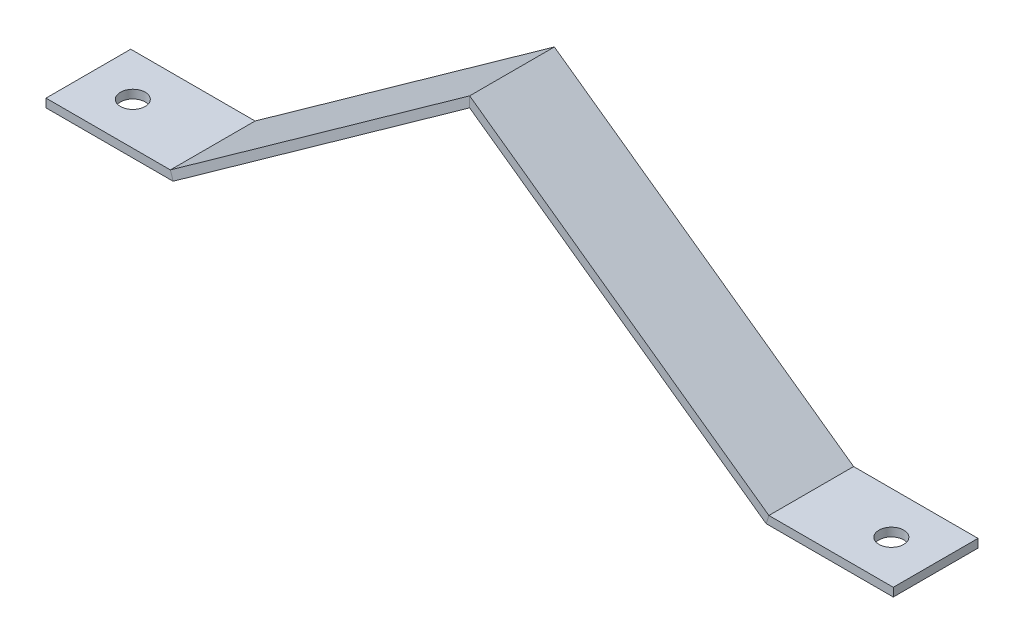
SolidWorks part; units mm, degrees
ref_plane "Front Plane" through (0, 0, 0) normal (0, 0, 1) x (1, 0, 0)
ref_plane "Top Plane" through (0, 0, 0) normal (0, 1, 0) x (1, 0, 0)
ref_plane "Right Plane" through (0, 0, 0) normal (1, 0, 0) x (0, 0, -1)
sketch "Sketch2" plane through (0, 0, 0) normal (0, 0, 1) x (1, 0, 0)
  line L0 (0, 0) -> (-3.81, 0)
  line L1 (-3.81, 0) -> (-12.7, 6.35)
  line L2 (-12.7, 6.35) -> (-21.59, 0)
  line L3 (-21.59, 0) -> (-25.4, 0)
  dimension "D1" = 25.4
  dimension "D2" = 17.78
  dimension "D3" = 8.89
  dimension "D4" = 6.35
  dimension "D5" = 3.81
sketch "Sketch3" plane through (0, 0, 0) normal (1, 0, 0) x (0, 0, -1)
  line L1 (0, 0) -> (2.54, 0)
  line L2 (0, 0) -> (0, 0.254)
  line L3 (0, 0.254) -> (2.54, 0.254)
  line L4 (2.54, 0) -> (2.54, 0.254)
  dimension "D1" = 2.54
  dimension "D2" = 0.254
sweep "Sweep1" add profiles "Sketch3" path "Sketch2"
hole_wizard "#69 (0.0292) Diameter Hole1" positions "Sketch5" profile "Sketch4" hole size "#69" standard "ANSI Inch" end condition through all
sketch "Sketch5" plane through (0, 0.254, 0) normal (0, 1, 0) x (1, 0, 0)
  line L0 (-21.6714, 0) -> (-25.4, 0) construction
  line L1 (-3.7286, 0) -> (0, 0) construction
  line L2 (-25.4, 0) -> (-25.4, 2.54) construction
  point P0 (-24.0665, 1.27)
  point P2 (-1.3272, 1.27)
  dimension "D1" = 1.27
  dimension "D2" = 1.27
  dimension "D3" = 22.7393
  dimension "D4" = 1.3335
sketch "Sketch4" plane through (-24.0665, 0.254, -1.27) normal (1, 0, 0) x (0, 0, 1)
  line L0 (0, 0) -> (0, 0.254)
  line L1 (0, 0.254) -> (0.3708, 0.254)
  line L2 (0.3708, 0.254) -> (0.3708, 0)
  line L5 (0.3708, 0) -> (0, 0)
  line L11 (0, -6.35) -> (0, 107.95) construction
  dimension "Thru Hole Dia." = 0.7417
  dimension "Thru Hole Depth" = 0.254
